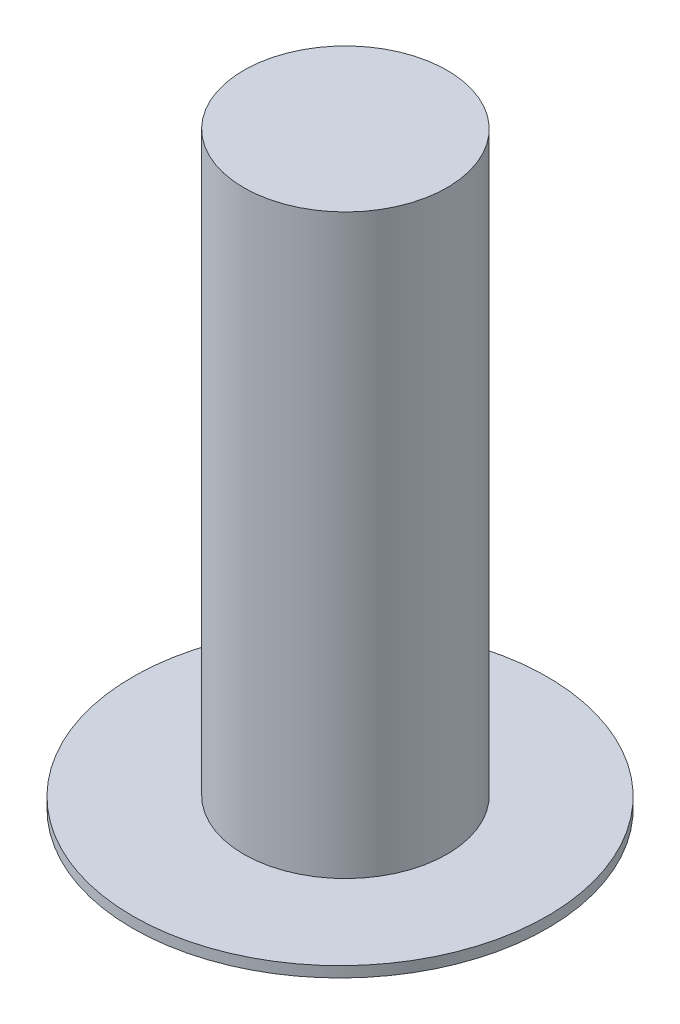
SolidWorks part; units mm, degrees
ref_plane "Front Plane" through (0, 0, 0) normal (0, 0, 1) x (1, 0, 0)
ref_plane "Top Plane" through (0, 0, 0) normal (0, 1, 0) x (1, 0, 0)
ref_plane "Right Plane" through (0, 0, 0) normal (1, 0, 0) x (0, 0, -1)
sketch "Sketch2" plane through (0, 0, 0) normal (0, 1, 0) x (1, 0, 0)
  circle A0 centre (-128.8529, 15.6006) radius 13.0403
  circle A1 centre (-128.8529, 15.6006) radius 5.5183
extrude "Boss-Extrude2" add sketch "Sketch2" along normal blind 0.6715
sketch "Sketch6" plane through (0, 0.6715, 0) normal (0, 1, 0) x (1, 0, 0)
  circle A0 centre (-128.7338, 15.8189) radius 6.3986
extrude "Boss-Extrude7" add sketch "Sketch6" along normal blind 36.322
sketch "Sketch8" plane through (0, 36.9935, 0) normal (0, 1, 0) x (1, 0, 0)
  circle A0 centre (-128.7735, 15.7792) radius 6.2142
  point P2 (-128.7735, 15.7792)
  point P3 (0, 0)
  point P4 (0, 0)
sketch "Sketch11" plane through (0, 36.9935, 0) normal (0, 1, 0) x (1, 0, 0)
